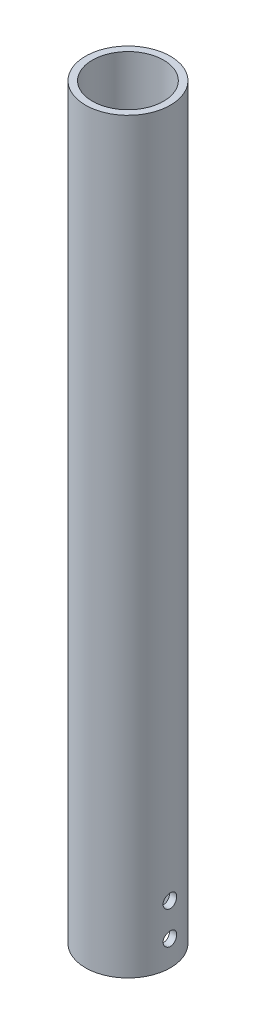
SolidWorks part; units mm, degrees
ref_plane "Спереди" through (0, 0, 0) normal (0, 0, 1) x (1, 0, 0)
ref_plane "Сверху" through (0, 0, 0) normal (0, 1, 0) x (1, 0, 0)
ref_plane "Справа" through (0, 0, 0) normal (1, 0, 0) x (0, 0, -1)
sketch "Эскиз1" plane through (0, 0, 0) normal (0, 1, 0) x (1, 0, 0)
  circle A0 centre (0, 0) radius 10.5
  circle A1 centre (0, 0) radius 12.5
extrude "Вытянуть1" add sketch "Эскиз1" along normal blind 220
sketch "Эскиз4" plane through (0, 0, 0) normal (1, 0, 0) x (0, 0, -1)
  line L0 (-12.5, 100) -> (-101.089, 100) construction
  circle A2 centre (0, 17.141) radius 2
  circle A3 centre (0, 7.4749) radius 2
extrude "Вырез-Вытянуть1" cut sketch "Эскиз4" against normal mid plane 200
